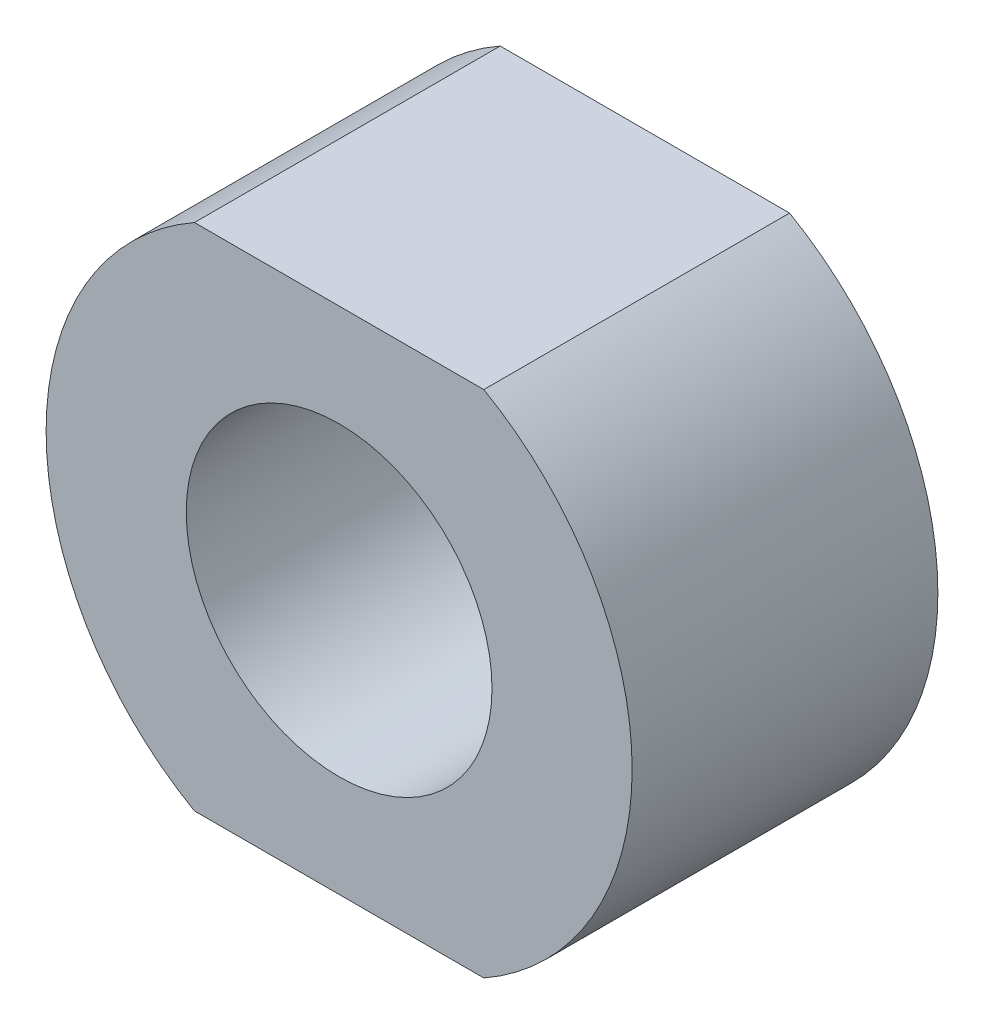
SolidWorks part; units mm, degrees
ref_plane "Plan de face" through (0, 0, 0) normal (0, 0, 1) x (1, 0, 0)
ref_plane "Plan de dessus" through (0, 0, 0) normal (0, 1, 0) x (1, 0, 0)
ref_plane "Plan de droite" through (0, 0, 0) normal (1, 0, 0) x (0, 0, -1)
sketch "Esquisse1" plane through (0, 0, 0) normal (0, 0, 1) x (1, 0, 0)
  circle A0 centre (0, 0) radius 5.75
  dimension "D1" = 11.5
extrude "Boss.-Extru.1" add sketch "Esquisse1" along normal blind 6
sketch "Esquisse2" plane through (0, 0, 6) normal (0, 0, 1) x (1, 0, 0)
  circle A0 centre (0, 0) radius 3
  dimension "D1" = 6
extrude "Enlèv. mat.-Extru.1" cut sketch "Esquisse2" against normal blind 6
sketch "Esquisse3" plane through (0, 0, 6) normal (0, 0, 1) x (1, 0, 0)
  line L0 (0, 0) -> (0, 5) construction
  line L1 (-3.8265, 6.1326) -> (3.8265, 6.1326)
  line L2 (-3.8265, 6.1326) -> (-3.8265, 5)
  line L3 (-3.8265, 5) -> (3.8265, 5)
  line L4 (3.8265, 6.1326) -> (3.8265, 5)
  line L5 (0, 0) -> (2.3571, 0) construction
  line L6 (-3.8265, -5) -> (3.8265, -5)
  line L7 (3.8265, -6.1326) -> (3.8265, -5)
  line L8 (-3.8265, -6.1326) -> (3.8265, -6.1326)
  line L9 (-3.8265, -6.1326) -> (-3.8265, -5)
  dimension "D1" = 5
extrude "Enlèv. mat.-Extru.2" cut sketch "Esquisse3" against normal through all
